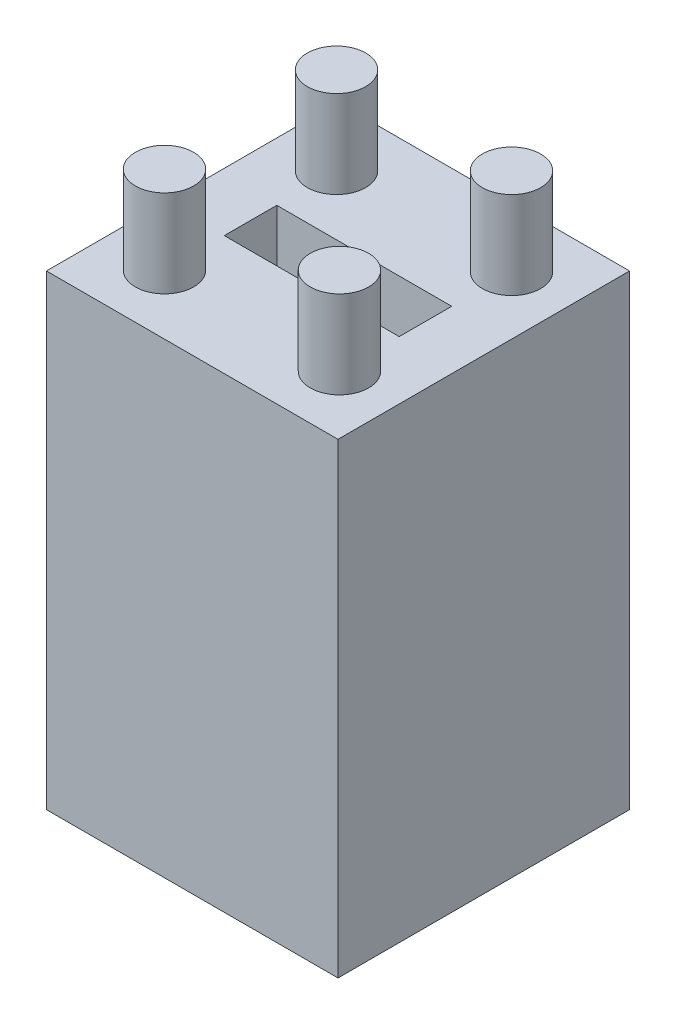
SolidWorks part; units mm, degrees
ref_plane "Front Plane" through (0, 0, 0) normal (0, 0, 1) x (1, 0, 0)
ref_plane "Top Plane" through (0, 0, 0) normal (0, 1, 0) x (1, 0, 0)
ref_plane "Right Plane" through (0, 0, 0) normal (1, 0, 0) x (0, 0, -1)
sketch "Sketch1" plane through (0, 0, 0) normal (0, 1, 0) x (1, 0, 0)
  line L1 (-31.75, 31.75) -> (31.75, 31.75)
  line L2 (-31.75, 31.75) -> (-31.75, -31.75)
  line L3 (-31.75, -31.75) -> (31.75, -31.75)
  line L4 (31.75, 31.75) -> (31.75, -31.75)
  line L5 (-31.75, 31.75) -> (31.75, -31.75) construction
  line L6 (-31.75, -31.75) -> (31.75, 31.75) construction
  point P0 (0, 0)
  dimension "D1" = 63.5
  dimension "D2" = 63.5
extrude "Boss-Extrude1" add sketch "Sketch1" along normal blind 101.6
sketch "Sketch3" plane through (0, 101.6, 0) normal (0, 1, 0) x (1, 0, 0)
  line L0 (19.05, 5.715) -> (19.05, -5.715)
  line L1 (19.05, 5.715) -> (-19.05, 5.715)
  line L2 (19.05, -5.715) -> (-19.05, -5.715)
  line L3 (-19.05, 5.715) -> (-19.05, -5.715)
  line L4 (31.75, -31.75) -> (31.75, 31.75) construction
  line L5 (-31.75, 31.75) -> (-31.75, -31.75) construction
  line L7 (19.05, 5.715) -> (31.75, 31.75) construction
  line L8 (19.05, -5.715) -> (31.75, -31.75) construction
  dimension "D1" = 12.7
  dimension "D2" = 11.43
  dimension "D3" = 12.7
extrude "Cut-Extrude1" cut sketch "Sketch3" against normal through all
sketch "Sketch5" plane through (0, 101.6, 0) normal (0, 1, 0) x (1, 0, 0)
  line L1 (-31.75, 31.75) -> (-31.75, -31.75) construction
  line L3 (31.75, -31.75) -> (31.75, 31.75) construction
  line L4 (19.05, -18.7325) -> (19.05, -31.75) construction
  line L5 (-31.75, -31.75) -> (31.75, -31.75) construction
  line L6 (19.05, -18.7325) -> (19.05, -5.715) construction
  line L7 (-19.05, -5.715) -> (19.05, -5.715) construction
  line L8 (19.05, -18.7325) -> (19.05, 18.7325) construction
  circle A1 centre (19.05, -18.7325) radius 6.35
  circle A2 centre (-19.05, -18.7325) radius 6.35
  circle A3 centre (-19.05, 18.7325) radius 6.35
  circle A4 centre (19.05, 18.7325) radius 6.35
  dimension "D1" = 6.35
  dimension "D2" = 12.7
  dimension "D3" = 2
  dimension "D6" = 6.35
  dimension "D5" = 37.465
  dimension "D4" = 2
extrude "Boss-Extrude2" add sketch "Sketch5" along normal blind 19.05
sketch "Sketch6" plane through (0, 0, 0) normal (0, -1, 0) x (1, 0, 0)
  line L0 (31.75, -31.75) -> (-31.75, -31.75) construction
  line L1 (31.75, 31.75) -> (31.75, -31.75) construction
  line L4 (18.542, -18.796) -> (18.542, -35.306) construction
  line L5 (-31.75, -31.75) -> (-31.75, 31.75) construction
  line L6 (18.542, -18.796) -> (18.542, -2.286) construction
  line L8 (18.542, -18.796) -> (18.542, 18.669) construction
  circle A1 centre (18.542, -18.796) radius 6.858
  circle A2 centre (-18.542, -18.796) radius 6.858
  circle A3 centre (-18.542, 18.669) radius 6.858
  circle A4 centre (18.542, 18.669) radius 6.858
  dimension "D1" = 6.35
  dimension "D2" = 13.716
  dimension "D3" = 2
  dimension "D6" = 6.35
  dimension "D5" = 37.465
  dimension "D7" = 12.954
  dimension "D4" = 2
extrude "Cut-Extrude3" cut sketch "Sketch6" against normal blind 19.05
